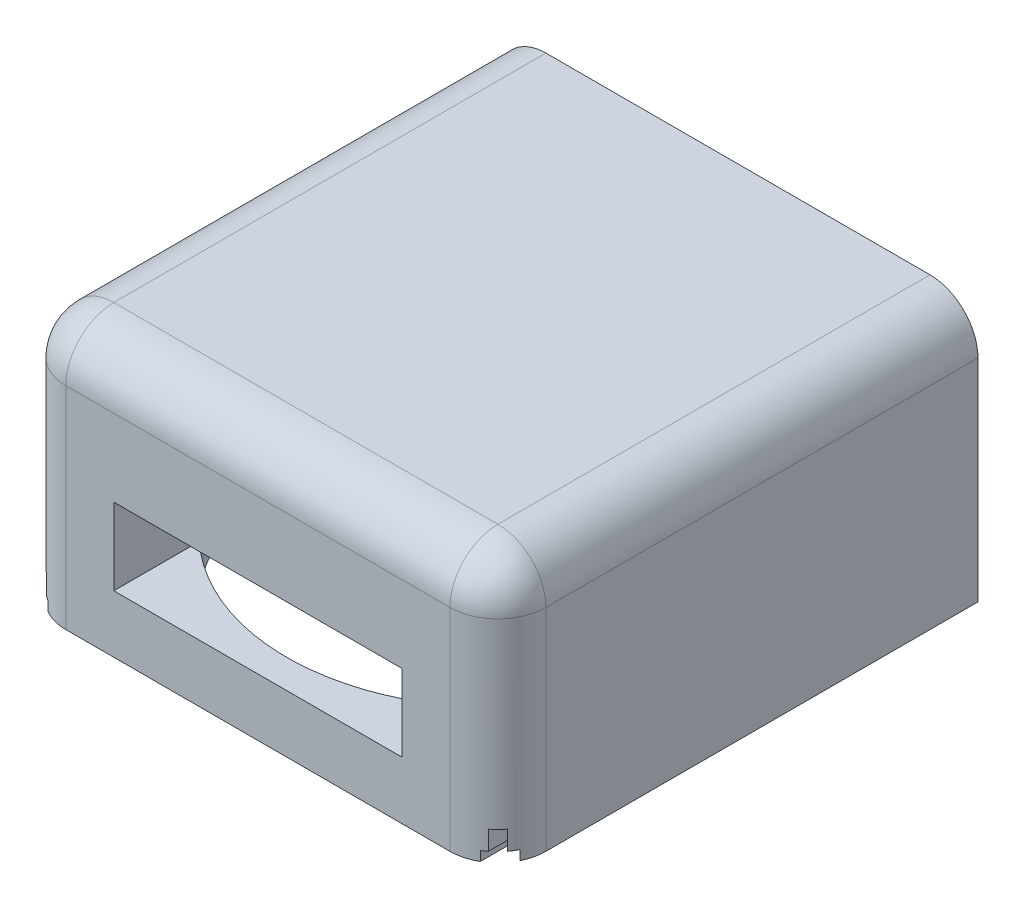
SolidWorks part; units mm, degrees
material "ABS"
ref_plane "Alzado" through (0, 0, 0) normal (0, 0, 1) x (1, 0, 0)
ref_plane "Planta" through (0, 0, 0) normal (0, 1, 0) x (1, 0, 0)
ref_plane "Vista lateral" through (0, 0, 0) normal (1, 0, 0) x (0, 0, -1)
sketch "Croquis1" plane through (0, 0, 0) normal (0, 1, 0) x (1, 0, 0)
  line L1 (-30, 12.5) -> (30, 12.5)
  line L2 (-30, 12.5) -> (-30, -12.5)
  line L3 (-30, -12.5) -> (30, -12.5)
  line L4 (30, 12.5) -> (30, -12.5)
  line L5 (-30, 12.5) -> (30, -12.5) construction
  line L6 (-30, -12.5) -> (30, 12.5) construction
  point P0 (0, 0)
  dimension "D1" = 60
  dimension "D2" = 25
extrude "Saliente-Extruir1" add sketch "Croquis1" along normal blind 25
sketch "Croquis2" plane through (0, 25, 0) normal (0, 1, 0) x (1, 0, 0)
  line L0 (30, 12.5) -> (-30, 12.5) construction
  circle A0 centre (0, 12.5) radius 22
extrude "Cortar-Extruir1" cut sketch "Croquis2" against normal blind 25
sketch "Croquis3" plane through (30, 0, 0) normal (1, 0, 0) x (0, 0, -1)
  line L1 (-18.9756, 27.7426) -> (20.3556, 27.7426)
  line L2 (-18.9756, 27.7426) -> (-18.9756, -4.8034)
  line L3 (-18.9756, -4.8034) -> (20.3556, -4.8034)
  line L4 (20.3556, 27.7426) -> (20.3556, -4.8034)
extrude "Cortar-Extruir6" cut sketch "Croquis3" against normal blind 5
sketch "Croquis6" plane through (-30, 0, 0) normal (-1, 0, 0) x (0, 0, 1)
  line L1 (-41.2115, 38.8228) -> (30.5427, 38.8228)
  line L2 (-41.2115, 38.8228) -> (-41.2115, -8.4927)
  line L3 (-41.2115, -8.4927) -> (30.5427, -8.4927)
  line L4 (30.5427, 38.8228) -> (30.5427, -8.4927)
extrude "Cortar-Extruir7" cut sketch "Croquis6" against normal blind 5
sketch "Croquis7" plane through (0, 25, 0) normal (0, 1, 0) x (1, 0, 0)
  line L1 (-25, 12.5) -> (25, 12.5)
  line L2 (-25, 12.5) -> (-25, -12.5)
  line L3 (-25, -12.5) -> (25, -12.5)
  line L4 (25, 12.5) -> (25, -12.5)
extrude "Saliente-Extruir2" add sketch "Croquis7" along normal blind 2
sketch "Croquis8" plane through (0, 0, -12.5) normal (0, 0, -1) x (-1, 0, 0)
  line L0 (-23.5, 0) -> (-23, 0)
  line L1 (-25, 0) -> (-22, 0) construction
  line L2 (-23, 0) -> (-23, 3)
  line L3 (-23, 3) -> (-24, 3)
  line L4 (-24, 3) -> (-24, 0)
  line L5 (-24, 0) -> (-23.5, 0)
  line L6 (0, 0) -> (0, 35.2787) construction
  line L7 (24, 0) -> (23.5, 0)
  line L8 (24, 3) -> (24, 0)
  line L9 (23, 3) -> (24, 3)
  line L10 (23, 0) -> (23, 3)
  line L11 (23.5, 0) -> (23, 0)
  dimension "D1" = 0.5
  dimension "D2" = 0.5
extrude "Cortar-Extruir9" cut sketch "Croquis8" against normal blind 38
sketch "Croquis10" plane through (0, 0, -12.5) normal (0, 0, -1) x (-1, 0, 0)
  line L12 (23, 0) -> (24, 0)
  line L13 (-22.4651, 0) -> (-22.4651, 1)
  line L14 (-24, 0) -> (-24.4651, 0)
  line L15 (23, 0) -> (22.4651, 0)
  line L16 (-24.4651, 1) -> (-24.4651, 0)
  line L17 (-24, 0) -> (-23, 0)
  line L18 (22.4651, 0) -> (22.4651, 1)
  line L19 (24.4651, 1) -> (24.4651, 0)
  line L20 (22.4651, 1) -> (24.4651, 1)
  line L21 (-22.4651, 1) -> (-24.4651, 1)
  line L22 (-23, 0) -> (-22.4651, 0)
  line L23 (24, 0) -> (24.4651, 0)
extrude "Cortar-Extruir11" cut sketch "Croquis10" against normal blind 31
sketch "Croquis11" plane through (0, 0, -12.5) normal (0, 0, -1) x (-1, 0, 0)
  line L0 (22.4651, 0) -> (22.4651, 1)
  line L1 (-24, 3) -> (-24, 1)
  line L2 (23, 3) -> (24, 3)
  line L3 (23, 3) -> (23, 1)
  line L4 (23, 1) -> (24, 1)
  line L5 (24, 3) -> (24, 1)
  line L6 (-23, 3) -> (-23, 1)
  line L7 (-24, 3) -> (-23, 3)
  line L8 (-24, 1) -> (-23, 1)
  line L9 (-24.5349, 0) -> (-24.5349, 1)
  line L11 (-24.7719, 3.438) -> (-22.4651, 3.438)
  line L12 (-24.7719, 3.438) -> (-24.7719, 0)
  line L13 (-24.7719, 0) -> (-22.4651, 0)
  line L14 (-22.4651, 3.438) -> (-22.4651, 0)
  line L15 (24.4651, 0) -> (22.356, 0)
  line L16 (24.4651, 0) -> (24.4651, 3.3824)
  line L17 (24.4651, 3.3824) -> (22.356, 3.3824)
  line L18 (22.356, 0) -> (22.356, 3.3824)
  line M2 (-24.4651, 0) -> (-24.4651, 1)
  line M3 (-24.4651, 1) -> (-24, 1)
  line M4 (-24, 1) -> (-24, 3)
  line M5 (-24, 3) -> (-23, 3)
  line M6 (-23, 3) -> (-23, 1)
  line M7 (-23, 1) -> (-22.4651, 1)
  line M8 (-22.4651, 1) -> (-22.4651, 0)
  line M14 (22.4651, 0) -> (22.4651, 1)
  line M15 (22.4651, 1) -> (23, 1)
  line M16 (23, 1) -> (23, 3)
  line M17 (23, 3) -> (24, 3)
  line M18 (24, 3) -> (24, 1)
  line M19 (24, 1) -> (24.4651, 1)
  line M20 (24.4651, 1) -> (24.4651, 0)
extrude "Saliente-Extruir3" add sketch "Croquis11" against normal blind 25 contours L15 L4 M20 M19 M15 M14 | L4 M16 M18 M17 | L13 L8 M2 M8 M7 M3 | L8 M4 M6 M5
sketch "Croquis12" plane through (0, 0, -12.5) normal (0, 0, -1) x (-1, 0, 0)
  line L0 (-25, 0) -> (-22, 0) construction
  line L1 (-22.5, 0) -> (-24.5, 0)
  line L2 (-22.5, 0) -> (-22.5, 1)
  line L3 (-22.5, 1) -> (-23, 1)
  line L4 (-24.5, 0) -> (-24.5, 1)
  line L5 (-25, 0) -> (-25, 27) construction
  line L6 (-22, 0) -> (-22, 25) construction
  line L7 (-24, 1) -> (-24.5, 1)
  line L8 (24, 3) -> (23, 3)
  line L9 (-23, 1) -> (-23, 3)
  line L10 (-23, 3) -> (-24, 3)
  line L11 (-24, 1) -> (-24, 3)
  line L12 (23, 1) -> (23, 3)
  line L13 (24.5, 0) -> (24.5, 1)
  line L14 (24.5, 0) -> (22.5, 0)
  line L15 (24, 1) -> (24, 3)
  line L16 (24.5, 1) -> (24, 1)
  line L17 (23, 1) -> (22.5, 1)
  line L18 (22.5, 0) -> (22.5, 1)
  dimension "D1" = 0.5
  dimension "D2" = 0.5
  dimension "D3" = 1
  dimension "D4" = 0.5
  dimension "D5" = 2
  dimension "D6" = 0.5
  dimension "D7" = 1
  dimension "D8" = 0.5
  dimension "D9" = 2
  dimension "D10" = 0.5
extrude "Cortar-Extruir12" cut sketch "Croquis12" against normal blind 25
sketch "Croquis13" plane through (0, 0, -12.5) normal (0, 0, -1) x (-1, 0, 0)
  line L0 (-22, 0) -> (-22.5, 0)
  line L1 (-22.5, 0) -> (-22.5, 1)
  line L2 (-22.5, 1) -> (-23, 1)
  line L3 (-23, 1) -> (-23, 3)
  line L4 (-23, 3) -> (-24, 3)
  line L5 (-24, 3) -> (-24, 1)
  line L6 (-24, 1) -> (-24.5, 1)
  line L7 (-24.5, 1) -> (-24.5, 0)
  line L8 (-24.5, 0) -> (-25, 0)
  line L9 (-25, 0) -> (-25, 27)
  line L10 (-25, 27) -> (25, 27)
  line L11 (25, 27) -> (25, 0)
  line L12 (25, 0) -> (24.5, 0)
  line L13 (24.5, 0) -> (24.5, 1)
  line L14 (24.5, 1) -> (24, 1)
  line L15 (24, 1) -> (24, 3) construction
  line L16 (24, 1) -> (24, 3)
  line L17 (24, 3) -> (23, 3)
  line L18 (23, 3) -> (23, 1)
  line L19 (23, 1) -> (22.5, 1)
  line L20 (22.5, 1) -> (22.5, 0)
  line L21 (22.5, 0) -> (22, 0)
  line L22 (22, 0) -> (22, 25)
  line L23 (22, 25) -> (-22, 25)
  line L24 (-22, 25) -> (-22, 0)
extrude "Saliente-Extruir4" add sketch "Croquis13" along normal blind 25
sketch "Croquis14" plane through (0, 0, 12.5) normal (0, 0, 1) x (1, 0, 0)
  line L0 (0, 0) -> (0, 6)
  line L1 (-15, 10) -> (-12.8352, 10)
  line L2 (-15, 6) -> (15, 6)
  line L3 (-15, 6) -> (-15, 14)
  line L4 (-15, 14) -> (15, 14)
  line L5 (15, 6) -> (15, 14)
  dimension "D1" = 6
  dimension "D2" = 8
  dimension "D3" = 15
  dimension "D4" = 30
  dimension "D5" = 30
extrude "Cortar-Extruir15" cut sketch "Croquis14" against normal blind 22
fillet "Redondeo4" radius 5 5 edges at (-25, 27, -12.5) (25, 27, -12.5)
fillet "Redondeo5" radius 5 5 edges at (-23.5355, 25.5355, 12.5) (23.5355, 25.5355, 12.5) (-25, 11, 12.5) (0, 27, 12.5) (25, 11, 12.5)
